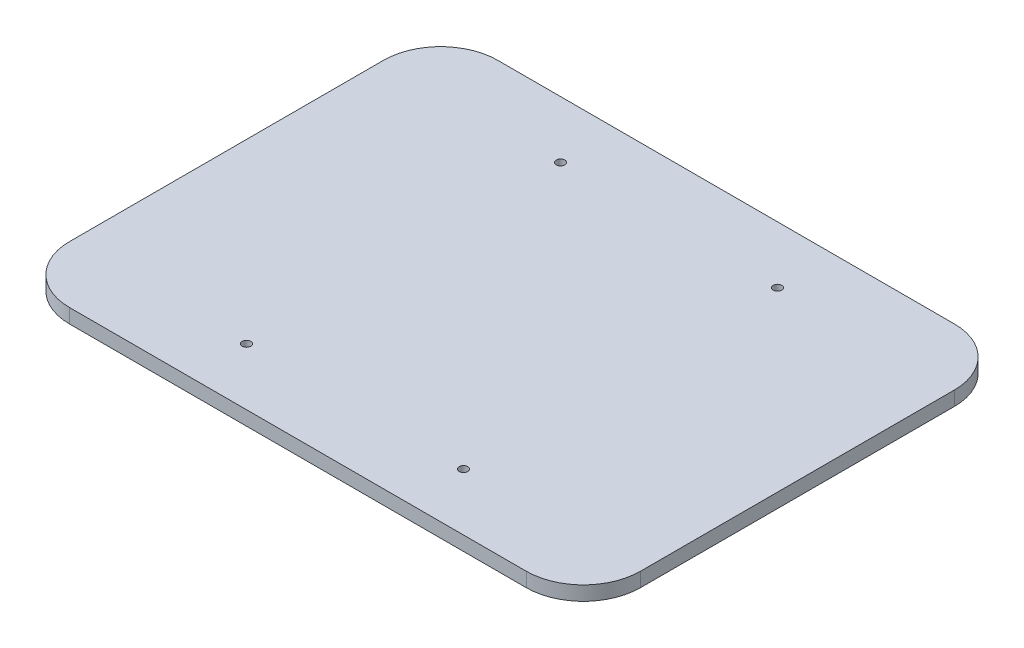
SolidWorks part; units mm, degrees
material "Acrílico (médio-alto impacto)"
ref_plane "Plano frontal" through (0, 0, 0) normal (0, 0, 1) x (1, 0, 0)
ref_plane "Plano superior" through (0, 0, 0) normal (0, 1, 0) x (1, 0, 0)
ref_plane "Plano direito" through (0, 0, 0) normal (1, 0, 0) x (0, 0, -1)
sketch "Esboço1" plane through (0, 0, 0) normal (0, 1, 0) x (1, 0, 0)
  line L1 (-40.816, 183.1145) -> (119.184, 183.1145)
  line L2 (-60.816, 163.1145) -> (-60.816, 53.1145)
  line L3 (-40.816, 33.1145) -> (119.184, 33.1145)
  line L4 (139.184, 163.1145) -> (139.184, 53.1145)
  arc A0 (119.184, 183.1145) -> (139.184, 163.1145) centre (119.184, 163.1145) cw
  arc A1 (119.184, 33.1145) -> (139.184, 53.1145) centre (119.184, 53.1145) ccw
  arc A2 (-60.816, 53.1145) -> (-40.816, 33.1145) centre (-40.816, 53.1145) ccw
  arc A3 (-40.816, 183.1145) -> (-60.816, 163.1145) centre (-40.816, 163.1145) ccw
  dimension "D1" = 20
extrude "Ressalto-extrusão1" add sketch "Esboço1" along normal blind 5
sketch "Esboço2" plane through (0, 5, 0) normal (0, 1, 0) x (1, 0, 0)
  line L0 (91.4945, 56.1145) -> (86.184, 56.1145) construction
  line L1 (-0.816, 170.1145) -> (79.184, 170.1145) construction
  line L2 (86.9299, 160.1145) -> (86.184, 160.1145) construction
  line L3 (3.7486, 46.1145) -> (83.7486, 46.1145) construction
  line L4 (84.184, 158.1145) -> (84.184, 58.1145) construction
  line L5 (-8.562, 160.1145) -> (-7.816, 160.1145) construction
  line L6 (-3.9974, 56.1145) -> (-7.816, 56.1145) construction
  line L7 (-5.816, 158.1145) -> (-5.816, 58.1145) construction
  line L10 (-60.816, 163.1145) -> (-60.816, 53.1145) construction
  line L11 (139.184, 53.1145) -> (139.184, 163.1145) construction
  line L12 (119.184, 183.1145) -> (-40.816, 183.1145) construction
  line L14 (-40.816, 33.1145) -> (119.184, 33.1145) construction
  arc A0 (88.8664, 162.6145) -> (79.184, 170.1145) centre (79.184, 160.1145) ccw construction
  arc A1 (83.7486, 46.1145) -> (93.431, 53.6145) centre (83.7486, 56.1145) ccw construction
  arc A2 (-10.4985, 162.6145) -> (-0.816, 170.1145) centre (-0.816, 160.1145) cw construction
  arc A3 (-5.9339, 53.6145) -> (3.7486, 46.1145) centre (3.7486, 56.1145) ccw construction
  arc A4 (91.4945, 56.1145) -> (93.431, 53.6145) centre (91.4945, 54.1145) cw construction
  arc A5 (84.184, 58.1145) -> (86.184, 56.1145) centre (86.184, 58.1145) ccw construction
  arc A6 (86.9299, 160.1145) -> (88.8664, 162.6145) centre (86.9299, 162.1145) ccw construction
  arc A7 (84.184, 158.1145) -> (86.184, 160.1145) centre (86.184, 158.1145) cw construction
  arc A8 (-7.816, 160.1145) -> (-5.816, 158.1145) centre (-7.816, 158.1145) cw construction
  arc A9 (-8.562, 160.1145) -> (-10.4985, 162.6145) centre (-8.562, 162.1145) cw construction
  arc A10 (-7.816, 56.1145) -> (-5.816, 58.1145) centre (-7.816, 58.1145) ccw construction
  arc A11 (-3.9974, 56.1145) -> (-5.9339, 53.6145) centre (-3.9974, 54.1145) ccw construction
  circle A12 centre (1.184, 163.1145) radius 1.5
  circle A13 centre (77.184, 163.1145) radius 1.5
  circle A14 centre (77.184, 53.1145) radius 1.5
  circle A15 centre (1.184, 53.1145) radius 1.5
  dimension "D1" = 10
  dimension "D2" = 2
  dimension "D9" = 7
  dimension "D10" = 7
  dimension "D11" = 3
  dimension "D12" = 7
  dimension "D13" = 7
  dimension "D14" = 3
  dimension "D15" = 7
  dimension "D16" = 7
  dimension "D17" = 3
  dimension "D3" = 100
  dimension "D4" = 55
  dimension "D5" = 100
  dimension "D6" = 55
  dimension "D7" = 13
  dimension "D8" = 13
extrude "Corte-extrusão1" cut sketch "Esboço2" against normal blind 10
